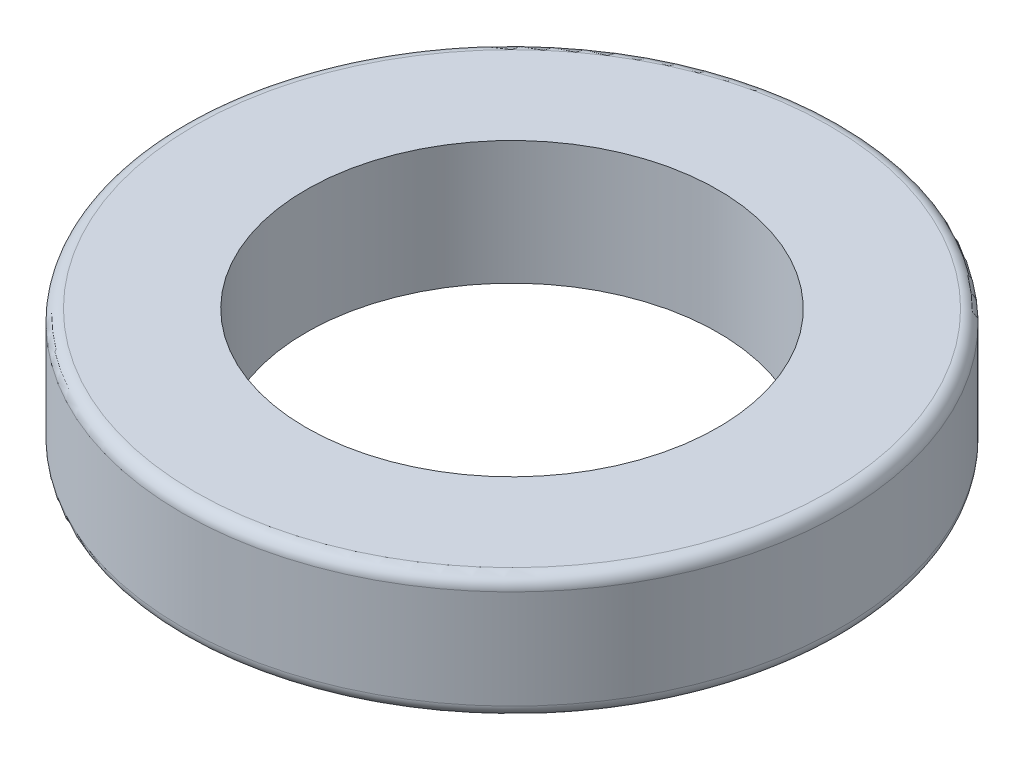
SolidWorks part; units mm, degrees
ref_plane "前视基准面" through (0, 0, 0) normal (0, 0, 1) x (1, 0, 0)
ref_plane "上视基准面" through (0, 0, 0) normal (0, 1, 0) x (1, 0, 0)
ref_plane "右视基准面" through (0, 0, 0) normal (1, 0, 0) x (0, 0, -1)
sketch "草图1" plane through (0, 0, 0) normal (0, 1, 0) x (1, 0, 0)
  circle A0 centre (0, 0) radius 5
  circle A1 centre (0, 0) radius 8
  dimension "D1" = 10
  dimension "D2" = 16
extrude "凸台-拉伸1" add sketch "草图1" along normal blind 3
fillet "圆角1" radius 0.3 2 edges at (0, 0, 8) (0, 3, 8)
